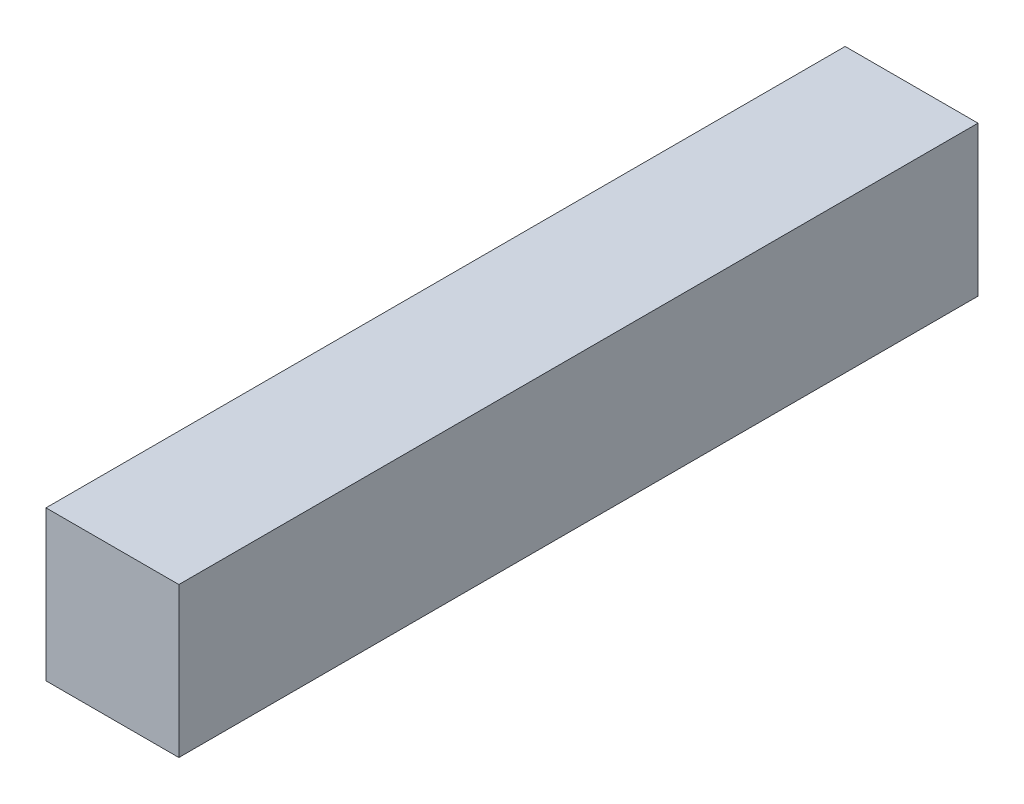
SolidWorks part; units mm, degrees
ref_plane "Front Plane" through (0, 0, 0) normal (0, 0, 1) x (1, 0, 0)
ref_plane "Top Plane" through (0, 0, 0) normal (0, 1, 0) x (1, 0, 0)
ref_plane "Right Plane" through (0, 0, 0) normal (1, 0, 0) x (0, 0, -1)
sketch "Sketch1" plane through (0, 0, 0) normal (0, 0, 1) x (1, 0, 0)
  line L1 (0, 0) -> (13.3, 0)
  line L2 (0, 0) -> (0, 15)
  line L3 (0, 15) -> (13.3, 15)
  line L4 (13.3, 0) -> (13.3, 15)
  dimension "D1" = 15
  dimension "D2" = 13.3
extrude "Boss-Extrude1" add sketch "Sketch1" along normal blind 80
